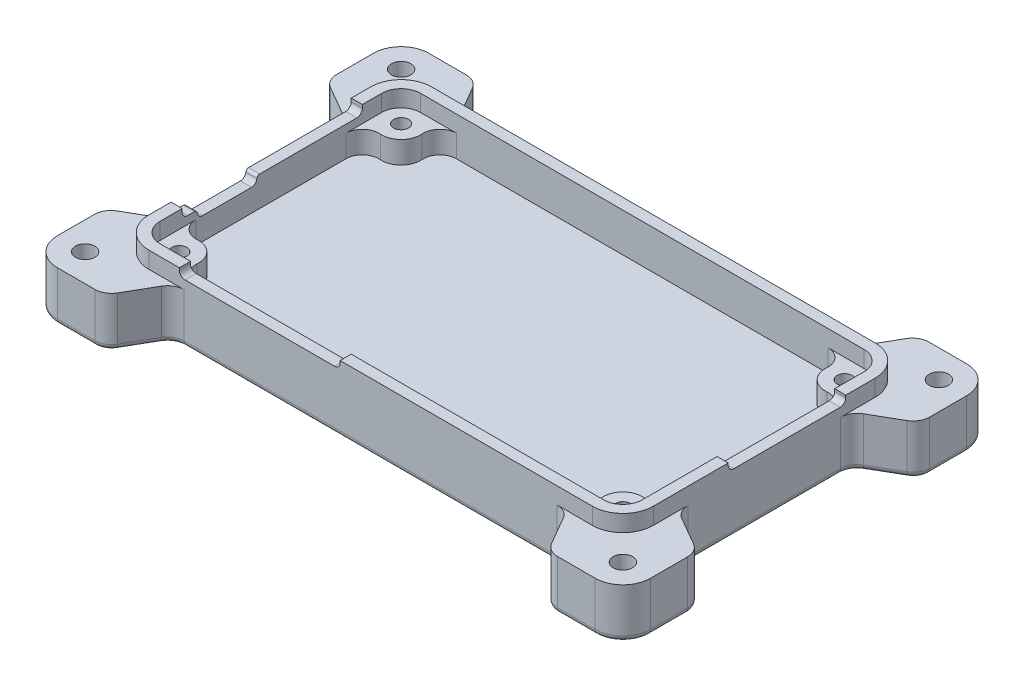
SolidWorks part; units mm, degrees
ref_plane "前视基准面" through (0, 0, 0) normal (0, 0, 1) x (1, 0, 0)
ref_plane "上视基准面" through (0, 0, 0) normal (0, 1, 0) x (1, 0, 0)
ref_plane "右视基准面" through (0, 0, 0) normal (1, 0, 0) x (0, 0, -1)
sketch "草图1" plane through (0, 0, 0) normal (0, 1, 0) x (1, 0, 0)
  line L0 (-40, 20) -> (40, 20) construction
  line L1 (-40, 20) -> (40, 20) construction
  line L2 (-40, 20) -> (-40, -20) construction
  line L3 (-40, -20) -> (40, -20) construction
  line L4 (40, 20) -> (40, -20) construction
  line L5 (-40, 20) -> (40, -20) construction
  line L6 (-40, -20) -> (40, 20) construction
  line L7 (-40, 20) -> (-40, -20) construction
  line L8 (-43.5, 20) -> (-43.5, -20)
  line L9 (-40, -23.5) -> (40, -23.5)
  line L10 (43.5, -20) -> (43.5, 20)
  line L11 (-40, 23.5) -> (40, 23.5)
  line L21 (-48.5, 33.5) -> (48.5, 33.5)
  line L22 (-53.5, 28.5) -> (-53.5, -28.5)
  line L23 (-48.5, -33.5) -> (48.5, -33.5)
  line L24 (53.5, 28.5) -> (53.5, -28.5)
  circle A0 centre (-40, -20) radius 1.35
  circle A1 centre (-40, 20) radius 1.35
  circle A2 centre (40, 20) radius 1.35
  circle A3 centre (40, -20) radius 1.35
  arc A4 (-40, 23.5) -> (-43.5, 20) centre (-40, 20) ccw
  arc A5 (43.5, 20) -> (40, 23.5) centre (40, 20) ccw
  arc A6 (40, -23.5) -> (43.5, -20) centre (40, -20) ccw
  arc A7 (-43.5, -20) -> (-40, -23.5) centre (-40, -20) ccw
  arc A16 (48.5, 33.5) -> (53.5, 28.5) centre (48.5, 28.5) cw
  arc A17 (53.5, -28.5) -> (48.5, -33.5) centre (48.5, -28.5) cw
  arc A18 (-48.5, -33.5) -> (-53.5, -28.5) centre (-48.5, -28.5) cw
  arc A19 (-53.5, 28.5) -> (-48.5, 33.5) centre (-48.5, 28.5) cw
  point P0 (0, 0)
  point P10 (0, 0)
  dimension "D1" = 2.7
  dimension "D4" = 7
  dimension "D10" = 10
  dimension "D12" = 5
  dimension "D2" = 80
  dimension "D3" = 10
  dimension "D7" = 80
  dimension "D8" = 40
  dimension "D9" = 10
  dimension "D11" = 10
  dimension "D5" = 2
  dimension "D6" = 2
extrude "凸台-拉伸1" add sketch "草图1" along normal blind 5
sketch "草图2" plane through (0, 5, 0) normal (0, 1, 0) x (1, 0, 0)
  line L0 (-43.5, 13.5193) -> (-43.5, -13.5193)
  line L1 (-33.5193, -23.5) -> (33.5193, -23.5)
  line L2 (43.5, -13.5193) -> (43.5, 13.5193)
  line L3 (33.5193, 23.5) -> (-33.5193, 23.5)
  line L13 (-53.5, 28.5) -> (-53.5, -28.5)
  line L14 (-53.5, 28.5) -> (-53.5, -28.5)
  line L15 (-48.5, -33.5) -> (48.5, -33.5)
  line L16 (-48.5, -33.5) -> (48.5, -33.5)
  line L21 (53.5, -28.5) -> (53.5, 28.5)
  line L22 (53.5, -28.5) -> (53.5, 28.5)
  line L23 (48.5, 33.5) -> (-48.5, 33.5)
  line L24 (48.5, 33.5) -> (-48.5, 33.5)
  arc A14 (-53.5, -28.5) -> (-48.5, -33.5) centre (-48.5, -28.5) ccw
  arc A15 (-48.5, 33.5) -> (-53.5, 28.5) centre (-48.5, 28.5) ccw
  arc A16 (-40.2692, 16.5104) -> (-36.5104, 20.2692) centre (-40, 20) ccw
  arc A17 (-36.5104, -20.2692) -> (-40.2692, -16.5104) centre (-40, -20) ccw
  arc A18 (36.5104, 20.2692) -> (40.2692, 16.5104) centre (40, 20) ccw
  arc A19 (40.2692, -16.5104) -> (36.5104, -20.2692) centre (40, -20) ccw
  arc A20 (36.5104, 20.2692) -> (33.5193, 23.5) centre (33.5193, 20.5) ccw
  arc A21 (-40.2692, -16.5104) -> (-43.5, -13.5193) centre (-40.5, -13.5193) cw
  arc A22 (36.5104, -20.2692) -> (33.5193, -23.5) centre (33.5193, -20.5) cw
  arc A23 (40.2692, -16.5104) -> (43.5, -13.5193) centre (40.5, -13.5193) ccw
  arc A24 (40.2692, 16.5104) -> (43.5, 13.5193) centre (40.5, 13.5193) cw
  arc A25 (-33.5193, -23.5) -> (-36.5104, -20.2692) centre (-33.5193, -20.5) cw
  arc A26 (-33.5193, 23.5) -> (-36.5104, 20.2692) centre (-33.5193, 20.5) ccw
  arc A27 (-40.2692, 16.5104) -> (-43.5, 13.5193) centre (-40.5, 13.5193) ccw
  circle A28 centre (40, -20) radius 1.35 construction
  circle A29 centre (40, 20) radius 1.35 construction
  circle A30 centre (-40, -20) radius 1.35 construction
  circle A31 centre (-40, 20) radius 1.35 construction
  circle A32 centre (40, -20) radius 1.35
  circle A33 centre (40, 20) radius 1.35
  circle A34 centre (-40, -20) radius 1.35
  circle A35 centre (-40, 20) radius 1.35
  arc A36 (-53.5, -28.5) -> (-48.5, -33.5) centre (-48.5, -28.5) ccw
  arc A37 (53.5, 28.5) -> (48.5, 33.5) centre (48.5, 28.5) ccw
  arc A39 (-48.5, 33.5) -> (-53.5, 28.5) centre (-48.5, 28.5) ccw
  arc A41 (53.5, 28.5) -> (48.5, 33.5) centre (48.5, 28.5) ccw
  arc A42 (48.5, -33.5) -> (53.5, -28.5) centre (48.5, -28.5) ccw
  arc A43 (48.5, -33.5) -> (53.5, -28.5) centre (48.5, -28.5) ccw
  dimension "D3" = 3
  dimension "D4" = 3
  dimension "D5" = 3
  dimension "D6" = 3
  dimension "D2" = 10
  dimension "D7" = 10
  dimension "D8" = 10
  dimension "D9" = 10
  dimension "D1" = 0
extrude "凸台-拉伸2" add sketch "草图2" along normal blind 4
sketch "草图3" plane through (0, 9, 0) normal (0, 1, 0) x (1, 0, 0)
  line L4 (-33.5193, -23.5) -> (33.5193, -23.5) construction
  line L6 (33.5193, 23.5) -> (-33.5193, 23.5) construction
  line L13 (43.5, -13.5193) -> (43.5, 13.5193) construction
  line L14 (-43.5, 13.5193) -> (-43.5, -13.5193) construction
  line L15 (-40, -25.5) -> (40, -25.5)
  line L44 (40, 25.5) -> (-40, 25.5)
  line L50 (45.5, -20) -> (45.5, 20)
  line L53 (-45.5, 20) -> (-45.5, -20)
  line L54 (43.5, -20) -> (43.5, 20)
  line L55 (40, 23.5) -> (-40, 23.5)
  line L56 (-43.5, 20) -> (-43.5, -20)
  line L57 (-40, -23.5) -> (40, -23.5)
  line L58 (40, 25.5) -> (-40, 25.5) construction
  line L59 (45.5, -20) -> (45.5, 20) construction
  line L60 (-40, -25.5) -> (40, -25.5) construction
  line L61 (-45.5, 20) -> (-45.5, -20) construction
  arc A14 (43.5, 20) -> (40, 23.5) centre (40, 20) ccw
  arc A15 (-43.5, 20) -> (-40, 23.5) centre (-40, 20) cw
  arc A16 (-40, -23.5) -> (-43.5, -20) centre (-40, -20) cw
  arc A17 (40, -23.5) -> (43.5, -20) centre (40, -20) ccw
  circle A18 centre (40, 20) radius 1.35 construction
  circle A19 centre (40, -20) radius 1.35 construction
  circle A20 centre (-40, 20) radius 1.35 construction
  circle A22 centre (-40, -20) radius 1.35 construction
  arc A25 (45.5, 20) -> (40, 25.5) centre (40, 20) ccw
  arc A26 (-45.5, 20) -> (-40, 25.5) centre (-40, 20) cw
  arc A28 (-45.5, 20) -> (-40, 25.5) centre (-40, 20) cw construction
  arc A29 (45.5, 20) -> (40, 25.5) centre (40, 20) ccw construction
  arc A30 (40, -25.5) -> (45.5, -20) centre (40, -20) ccw construction
  arc A31 (-40, -25.5) -> (-45.5, -20) centre (-40, -20) cw construction
  arc A32 (45.5, -20) -> (40, -25.5) centre (40, -20) cw
  arc A33 (-40, -25.5) -> (-45.5, -20) centre (-40, -20) cw
  dimension "D1" = 2
  dimension "D2" = 2
extrude "凸台-拉伸3" add sketch "草图3" along normal blind 3
sketch "草图8" plane through (-45.5, 0, 0) normal (-1, 0, 0) x (0, 0, 1)
  line L0 (33.5, 9) -> (33.5, 0) construction
  line L5 (-20, 9) -> (20, 9) construction
  line L11 (-16.5, 12) -> (16, 12)
  line L12 (-16.5, 12) -> (-16.5, 11.4)
  line L13 (-15.5, 10.4) -> (15, 10.4)
  line L14 (16, 12) -> (16, 11.4)
  line L15 (-20, 12) -> (20, 12) construction
  line L17 (-25.5, 12) -> (-25.5, 9) construction
  arc A2 (16, 11.4) -> (15, 10.4) centre (15, 11.4) cw
  arc A3 (-15.5, 10.4) -> (-16.5, 11.4) centre (-15.5, 11.4) cw
  dimension "D3" = 17.5
  dimension "D1" = 1
  dimension "D2" = 9
  dimension "D4" = 1.4
extrude "切除-拉伸4" cut sketch "草图8" against normal blind 3
sketch "草图9" plane through (0, 0, 25.5) normal (0, 0, 1) x (1, 0, 0)
  line L0 (-45.5, 12) -> (-45.5, 9) construction
  line L1 (-34.5, 12) -> (-5.5, 12)
  line L2 (-34.5, 12) -> (-34.5, 11.6)
  line L3 (-33.5, 10.6) -> (-6.5, 10.6)
  line L4 (-5.5, 12) -> (-5.5, 11.6)
  line L5 (45.5, 12) -> (45.5, 9) construction
  line L6 (-40, 12) -> (40, 12) construction
  line L7 (-40, 9) -> (40, 9) construction
  arc A0 (-34.5, 11.6) -> (-33.5, 10.6) centre (-33.5, 11.6) ccw
  arc A1 (-5.5, 11.6) -> (-6.5, 10.6) centre (-6.5, 11.6) cw
  point P16 (-5.5, 10.6)
  dimension "D3" = 1
  dimension "D1" = 11
  dimension "D2" = 51
  dimension "D4" = 1.6
extrude "切除-拉伸5" cut sketch "草图9" against normal blind 3
sketch "草图10" plane through (45.5, 0, 0) normal (1, 0, 0) x (0, 0, -1)
  line L0 (-20, 12) -> (20, 12) construction
  line L1 (-6.5, 12) -> (14.7, 12)
  line L2 (-6.5, 12) -> (-6.5, 11.6)
  line L3 (-5.5, 10.6) -> (13.7, 10.6)
  line L4 (14.7, 12) -> (14.7, 11.6)
  line L5 (-20, 9) -> (20, 9) construction
  line L7 (25.5, 12) -> (25.5, 9) construction
  line L8 (-20, 9) -> (20, 9) construction
  line L10 (-33.5, 9) -> (-33.5, 0) construction
  arc A0 (14.7, 11.6) -> (13.7, 10.6) centre (13.7, 11.6) cw
  arc A1 (-5.5, 10.6) -> (-6.5, 11.6) centre (-5.5, 11.6) cw
  point P14 (16, 9)
  dimension "D3" = 1
  dimension "D1" = 27
  dimension "D2" = 10.8
  dimension "D4" = 1.6
extrude "切除-拉伸6" cut sketch "草图10" against normal blind 3
sketch "草图13" plane through (0, 9, 0) normal (0, 1, 0) x (1, 0, 0)
  line L0 (-45.5, 15.5) -> (-45.5, -15.5)
  line L1 (-62.5491, 0) -> (69.3801, 0) construction
  line L2 (-43.5, -13.5193) -> (-43.5, -20) construction
  line L3 (-53.5, 28.5) -> (-53.5, -28.5) construction
  line L4 (-53.5, 20.1188) -> (-53.5, -20.1188)
  line L5 (-53.5, 20.1188) -> (-45.5, 15.5)
  line L6 (-43.5, 15.5) -> (-45.5, 15.5) construction
  line L7 (-53.5, -20.1188) -> (-45.5, -15.5)
  line L8 (0, 45.8208) -> (0, -47.5614) construction
  line L9 (53.5, 20.1188) -> (45.5, 15.5)
  line L10 (45.5, 15.5) -> (45.5, -15.5)
  line L11 (53.5, -20.1188) -> (45.5, -15.5)
  line L12 (53.5, 20.1188) -> (53.5, -20.1188)
  line L13 (-40, 33.5) -> (-35.3812, 25.5)
  line L14 (48.5, 33.5) -> (-48.5, 33.5) construction
  line L15 (40, 25.5) -> (-40, 25.5) construction
  line L16 (-35.3812, 25.5) -> (35.3812, 25.5)
  line L17 (40, 25.5) -> (-40, 25.5) construction
  line L18 (35.3812, 25.5) -> (40, 33.5)
  line L19 (40, 33.5) -> (-40, 33.5)
  line L20 (35.3812, -25.5) -> (40, -33.5)
  line L21 (-35.3812, -25.5) -> (35.3812, -25.5)
  line L22 (-40, -33.5) -> (-35.3812, -25.5)
  line L23 (40, -33.5) -> (-40, -33.5)
  line L24 (-45.5, 20) -> (-45.5, -20) construction
  dimension "D1" = 60
  dimension "D2" = 60
  dimension "D3" = 60
  dimension "D4" = 60
  dimension "D5" = 80
extrude "切除-拉伸9" cut sketch "草图13" against normal through all
fillet "圆角2" radius 3 16 edges at (45.5, 4.5, -15.5) (53.5, 4.5, -20.1188) (-45.5, 4.5, -15.5) (-53.5, 4.5, -20.1188) (45.5, 4.5, 15.5) (-45.5, 4.5, 15.5) (53.5, 4.5, 20.1188) (-53.5, 4.5, 20.1188) (40, 4.5, 33.5) (35.3812, 4.5, 25.5) (-35.3812, 4.5, 25.5) (-40, 4.5, 33.5) (40, 4.5, -33.5) (35.3812, 4.5, -25.5) (-35.3812, 4.5, -25.5) (-40, 4.5, -33.5)
sketch "草图14" plane through (0, 9, 0) normal (0, 1, 0) x (1, 0, 0)
  line L0 (0, 53.515) -> (0, -42.2469) construction
  circle A0 centre (-48.5, 28.5) radius 1.75
  arc A1 (-48.5, 33.5) -> (-53.5, 28.5) centre (-48.5, 28.5) ccw construction
  circle A2 centre (-48.5, -28.5) radius 1.75
  arc A3 (-53.5, -28.5) -> (-48.5, -33.5) centre (-48.5, -28.5) ccw construction
  circle A4 centre (48.5, -28.5) radius 1.75
  circle A5 centre (48.5, 28.5) radius 1.75
  dimension "D1" = 3.5
extrude "切除-拉伸10" cut sketch "草图14" against normal through all
fillet "圆角4" radius 1 40 edges at (-45.9019, 0, 15.2679) (-49.5, 0, 17.8094) (-53.0981, 0, 20.3509) (-53.5, 0, 25.1754) (-52.0355, 0, 32.0355) (-45.116, 0, 33.5) (-40.2321, 0, 33.0981) (-37.6906, 0, 29.5) (-35.1491, 0, 25.9019) (0, 0, 25.5) (35.1491, 0, 25.9019) (37.6906, 0, 29.5) (40.2321, 0, 33.0981) (45.116, 0, 33.5) (52.0355, 0, 32.0355) (53.5, 0, 25.1754) (53.0981, 0, 20.3509) (49.5, 0, 17.8094) (45.9019, 0, 15.2679) (45.5, 0, 0) (45.9019, 0, -15.2679) (49.5, 0, -17.8094) (53.0981, 0, -20.3509) (53.5, 0, -25.1754) (52.0355, 0, -32.0355) (45.116, 0, -33.5) (40.2321, 0, -33.0981) (37.6906, 0, -29.5) (35.1491, 0, -25.9019) (0, 0, -25.5) (-35.1491, 0, -25.9019) (-37.6906, 0, -29.5) (-40.2321, 0, -33.0981) (-45.116, 0, -33.5) (-52.0355, 0, -32.0355) (-53.5, 0, -25.1754) (-53.0981, 0, -20.3509) (-49.5, 0, -17.8094) (-45.9019, 0, -15.2679) (-45.5, 0, 0)
sketch "草图16" plane through (-45.5, 0, 0) normal (-1, 0, 0) x (0, 0, 1)
  line L0 (2.5, 10.4) -> (2.5, 9.05)
  line L1 (-15.5, 10.4) -> (15, 10.4) construction
  line L2 (2.5, 9.05) -> (13.3, 9.05)
  line L3 (13.3, 9.05) -> (13.3, 10.4)
  line L4 (13.3, 10.4) -> (2.5, 10.4)
  line L5 (16, 11.4) -> (16, 12) construction
  dimension "D1" = 1.35
  dimension "D2" = 13.5
  dimension "D3" = 10.8
extrude "切除-拉伸12" cut sketch "草图16" against normal blind 2
fillet "圆角6" radius 1 2 edges at (-44.5, 9.05, 13.3) (-44.5, 9.05, 2.5)
fillet "圆角7" radius 0.5 2 edges at (-44.5, 10.4, 2.5) (-44.5, 10.4, 13.3)
